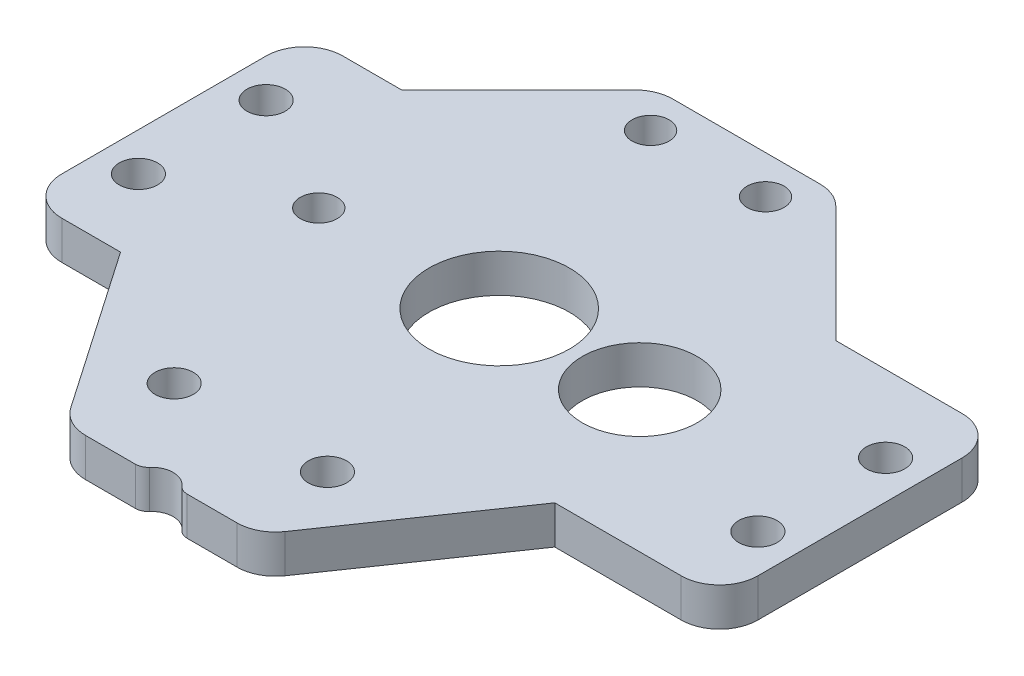
SolidWorks part; units mm, degrees
material "Aleación 6061"
ref_plane "Alzado" through (0, 0, 0) normal (0, 0, 1) x (1, 0, 0)
ref_plane "Planta" through (0, 0, 0) normal (0, 1, 0) x (1, 0, 0)
ref_plane "Vista lateral" through (0, 0, 0) normal (1, 0, 0) x (0, 0, -1)
sketch "Croquis base" plane through (0, 0, 0) normal (0, 1, 0) x (1, 0, 0)
  line L0 (-19.65, 11) -> (-19.65, -11) construction
  line L1 (-27.25, 11) -> (-19.65, 11)
  line L2 (-27.25, 11) -> (-27.25, -11)
  line L3 (-27.25, -11) -> (-19.65, -11)
  line L4 (27.25, 11) -> (27.25, -11)
  line L5 (-27.25, 11) -> (27.25, -11) construction
  line L6 (-27.25, -11) -> (27.25, 11) construction
  line L7 (14.35, 11) -> (14.35, -11) construction
  line L8 (-9.65, 21) -> (4.35, 21)
  line L9 (-19.65, 11) -> (-9.65, 21)
  line L10 (14.35, 11) -> (4.35, 21)
  line L11 (-10.15, -24.8) -> (4.85, -24.8)
  line L12 (-2.65, 21) -> (-2.65, -24.8) construction
  line L13 (-10.15, -24.8) -> (-19.65, -11)
  line L14 (4.85, -24.8) -> (14.35, -11)
  line L15 (14.35, -11) -> (27.25, -11)
  line L16 (14.35, 11) -> (27.25, 11)
  point P0 (0, 0)
  dimension "D1" = 22
  dimension "D2" = 54.5
  dimension "D3" = 7.6
  dimension "D4" = 12.9
  dimension "D5" = 10
  dimension "D6" = 45
  dimension "D7" = 45
  dimension "D8" = 13.8
  dimension "D9" = 15
extrude "Saliente-Extruir1" add sketch "Croquis base" along normal blind 3
sketch "Croquis barridos" plane through (0, 3, 0) normal (0, 1, 0) x (1, 0, 0)
  line L0 (-27.25, 0) -> (27.25, 0) construction
  line L1 (-27.25, 11) -> (-27.25, -11) construction
  line L2 (27.25, -11) -> (27.25, 11) construction
  line L3 (0, 21) -> (0, -24.8) construction
  line L4 (4.35, 21) -> (-9.65, 21) construction
  line L5 (-10.15, -24.8) -> (4.85, -24.8) construction
  line L6 (-2.65, 21) -> (-2.65, -24.8) construction
  line L7 (-19.65, -11) -> (14.35, -11) construction
  line L8 (-19.65, 11) -> (14.35, 11) construction
  line L9 (-4.432, -23.877) -> (-0.4487, -23.877) construction
  line L10 (-1.15, -23.877) -> (-1.15, -24.8) construction
  line L11 (-4.15, -23.877) -> (-4.15, -24.8) construction
  line L12 (-4.15, -24.8) -> (-1.15, -24.8)
  line L13 (-27.25, -11) -> (-19.65, -11) construction
  circle A0 centre (-14.88, -0.25) radius 1.45
  circle A1 centre (-1, 0) radius 5.5
  circle A2 centre (10, 0) radius 4.5
  circle A3 centre (-24.25, 5) radius 1.5
  circle A4 centre (24.25, 5) radius 1.5
  circle A5 centre (24.25, -5) radius 1.5
  circle A6 centre (-24.25, -5) radius 1.5
  circle A7 centre (-8.65, -17.8) radius 1.5
  circle A8 centre (-7.15, 18) radius 1.45
  circle A9 centre (3.35, -17.8) radius 1.5
  circle A10 centre (1.85, 18) radius 1.45
  arc A11 (-4.15, -24.8) -> (-1.15, -24.8) centre (-2.65, -25.5574) cw
  dimension "D4" = 2.9
  dimension "D5" = 11
  dimension "D6" = 9
  dimension "D9" = 3
  dimension "D13" = 3
  dimension "D16" = 2.9
  dimension "D2" = 17.25
  dimension "D3" = 28.25
  dimension "D7" = 3
  dimension "D8" = 5
  dimension "D10" = 27.25
  dimension "D11" = 6.8
  dimension "D12" = 6
  dimension "D14" = 4.5
  dimension "D15" = 7
  dimension "D17" = 0.923
  dimension "D18" = 1.5
  dimension "D19" = 1.5
  dimension "D20" = 10.75
  dimension "D21" = 12.37
extrude "Cortar-Extruir1" cut sketch "Croquis barridos" against normal blind 3
fillet "Redondeo1" radius 3 8 edges at (27.25, 1.5, -11) (-27.25, 1.5, -11) (27.25, 1.5, 11) (-27.25, 1.5, 11) (-9.65, 1.5, -21) (4.35, 1.5, -21) (4.85, 1.5, 24.8) (-10.15, 1.5, 24.8)
fillet "Redondeo2" radius 1 2 edges at (-4.15, 1.5, 24.8) (-1.15, 1.5, 24.8)
